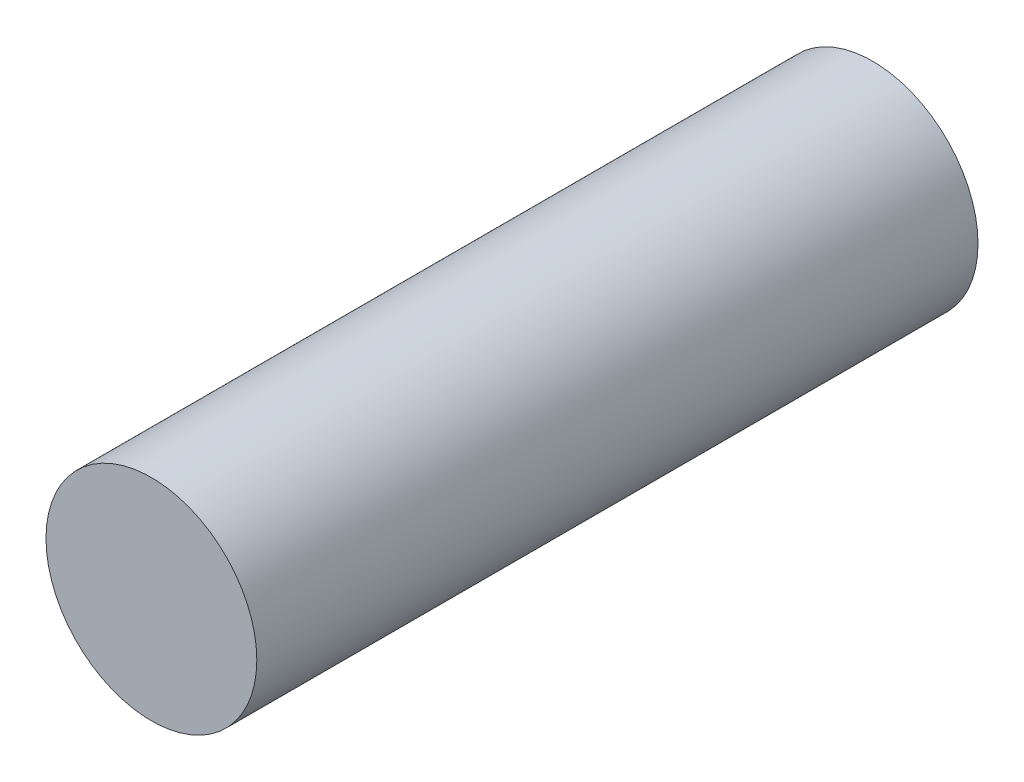
SolidWorks part; units mm, degrees
ref_plane "Plan de face" through (0, 0, 0) normal (0, 0, 1) x (1, 0, 0)
ref_plane "Plan de dessus" through (0, 0, 0) normal (0, 1, 0) x (1, 0, 0)
ref_plane "Plan de droite" through (0, 0, 0) normal (1, 0, 0) x (0, 0, -1)
sketch "Esquisse1" plane through (0, 0, 0) normal (0, 0, 1) x (1, 0, 0)
  circle A0 centre (0, 0) radius 9.5
  dimension "D1" = 19
extrude "Boss.-Extru.1" add sketch "Esquisse1" along normal blind 65
